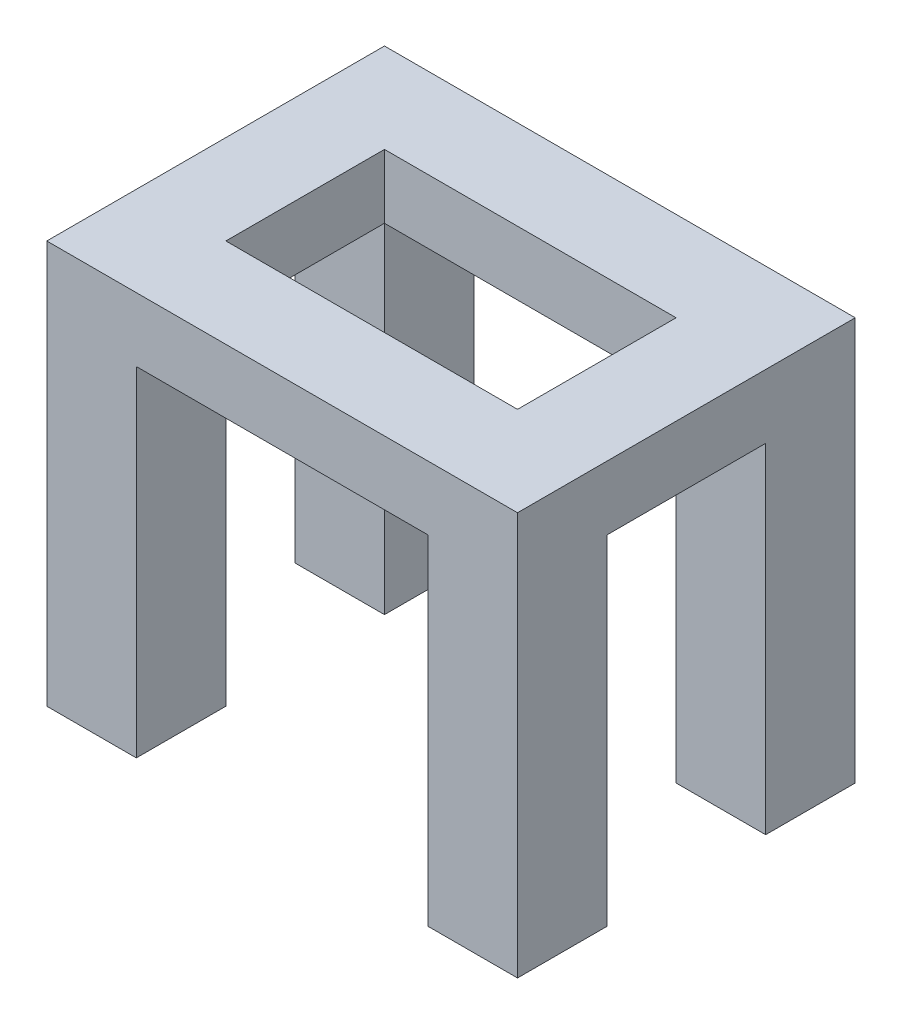
SolidWorks part; units mm, degrees
ref_plane "Front Plane" through (0, 0, 0) normal (0, 0, 1) x (1, 0, 0)
ref_plane "Top Plane" through (0, 0, 0) normal (0, 1, 0) x (1, 0, 0)
ref_plane "Right Plane" through (0, 0, 0) normal (1, 0, 0) x (0, 0, -1)
sketch "Sketch1" plane through (0, 0, 0) normal (0, 1, 0) x (1, 0, 0)
  line L0 (-16.4197, 14.2521) -> (20.3803, 14.2521)
  line L1 (-9.4197, 7.2521) -> (13.3803, 7.2521)
  line L2 (-9.4197, 7.2521) -> (-9.4197, -5.1479)
  line L3 (-9.4197, -5.1479) -> (13.3803, -5.1479)
  line L4 (13.3803, 7.2521) -> (13.3803, -5.1479)
  line L5 (20.3803, 14.2521) -> (20.3803, -12.1479)
  line L6 (-16.4197, -12.1479) -> (20.3803, -12.1479)
  line L7 (-16.4197, 14.2521) -> (-16.4197, -12.1479)
  dimension "D1" = 22.8
  dimension "D2" = 12.4
  dimension "D3" = 7
extrude "Boss-Extrude1" add sketch "Sketch1" along normal blind 5
sketch "Sketch2" plane through (0, 0, 0) normal (0, -1, 0) x (1, 0, 0)
  line L1 (20.3803, -14.2521) -> (13.3803, -14.2521)
  line L2 (20.3803, -14.2521) -> (20.3803, -7.2521)
  line L3 (20.3803, -7.2521) -> (13.3803, -7.2521)
  line L4 (13.3803, -14.2521) -> (13.3803, -7.2521)
  line L5 (-9.4197, -7.2521) -> (-16.4197, -7.2521)
  line L6 (-9.4197, -7.2521) -> (-9.4197, -14.2521)
  line L7 (-9.4197, -14.2521) -> (-16.4197, -14.2521)
  line L8 (-16.4197, -7.2521) -> (-16.4197, -14.2521)
  line L9 (-16.4197, 12.1479) -> (-9.4197, 12.1479)
  line L10 (-16.4197, 12.1479) -> (-16.4197, 5.1479)
  line L11 (-16.4197, 5.1479) -> (-9.4197, 5.1479)
  line L12 (-9.4197, 12.1479) -> (-9.4197, 5.1479)
  line L13 (20.3803, 12.1479) -> (13.3803, 12.1479)
  line L14 (20.3803, 12.1479) -> (20.3803, 5.1479)
  line L15 (20.3803, 5.1479) -> (13.3803, 5.1479)
  line L16 (13.3803, 12.1479) -> (13.3803, 5.1479)
extrude "Boss-Extrude2" add sketch "Sketch2" along normal blind 26.5
